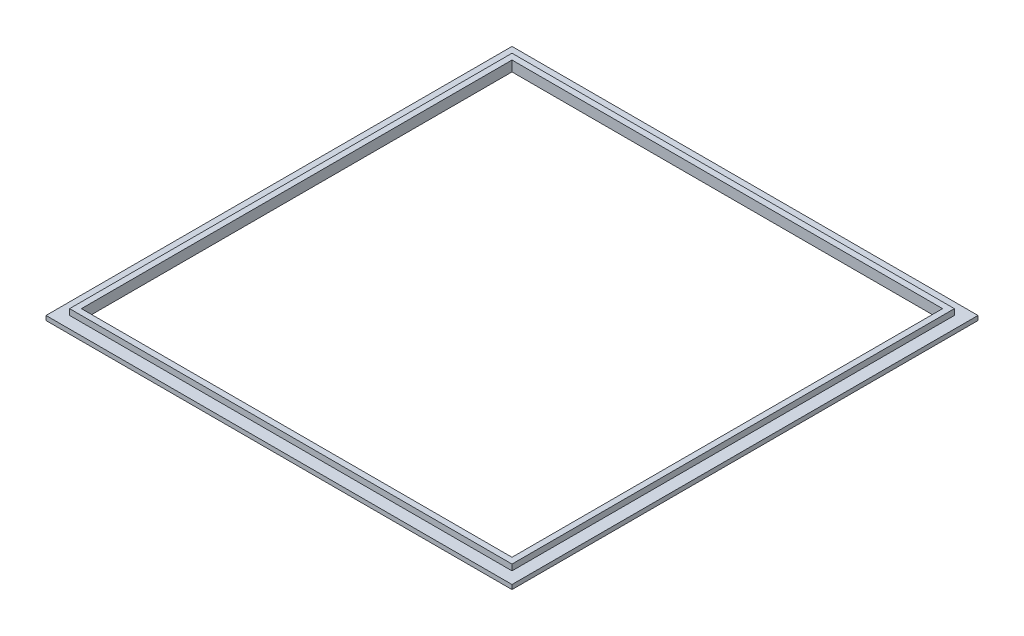
SolidWorks part; units mm, degrees
ref_plane "Alzado" through (0, 0, 0) normal (0, 0, 1) x (1, 0, 0)
ref_plane "Planta" through (0, 0, 0) normal (0, 1, 0) x (1, 0, 0)
ref_plane "Vista lateral" through (0, 0, 0) normal (1, 0, 0) x (0, 0, -1)
sketch "Croquis1" plane through (0, 0, 0) normal (0, 1, 0) x (1, 0, 0)
  line L0 (-6, -6) -> (-6, 152)
  line L1 (0, 0) -> (146, 0)
  line L2 (0, 0) -> (0, 146)
  line L3 (0, 146) -> (146, 146)
  line L4 (146, 0) -> (146, 146)
  line L5 (-6, 152) -> (152, 152)
  line L6 (152, -6) -> (152, 152)
  line L7 (-6, -6) -> (152, -6)
  dimension "D1" = 146
  dimension "D2" = 6
extrude "Saliente-Extruir1" add sketch "Croquis1" along normal blind 1.5
sketch "Croquis2" plane through (0, 1.5, 0) normal (0, 1, 0) x (1, 0, 0)
  line L0 (146, 0) -> (146, 146) construction
  line L1 (0, 0) -> (146, 0) construction
  line L2 (0, 146) -> (0, 0) construction
  line L3 (146, 146) -> (0, 146) construction
  line L4 (146, 0) -> (146, 146)
  line L5 (0, 0) -> (146, 0)
  line L6 (0, 146) -> (0, 0)
  line L7 (146, 146) -> (0, 146)
  line L8 (148, 148) -> (-2, 148)
  line L9 (-2, 148) -> (-2, -2)
  line L10 (-2, -2) -> (148, -2)
  line L11 (148, -2) -> (148, 148)
  dimension "D1" = 2
extrude "Saliente-Extruir2" add sketch "Croquis2" along normal blind 2
